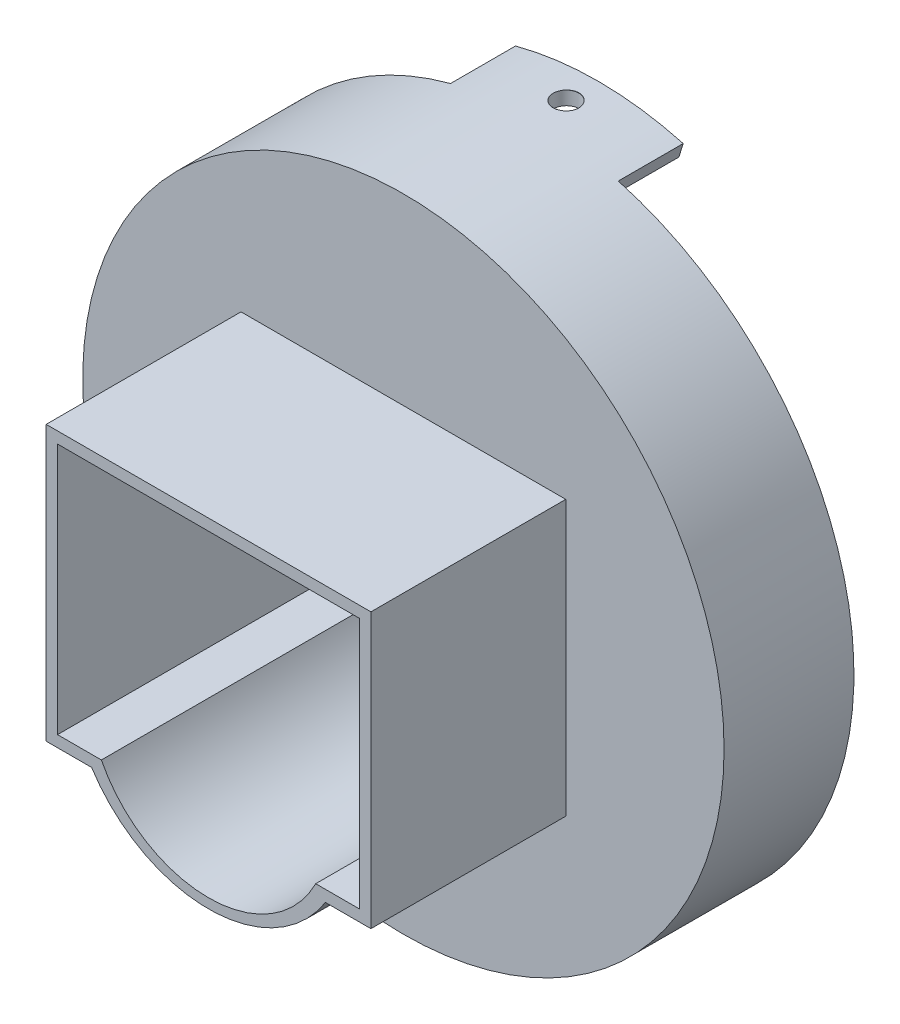
SolidWorks part; units mm, degrees
material "ABS"
ref_plane "Front Plane" through (0, 0, 0) normal (0, 0, 1) x (1, 0, 0)
ref_plane "Top Plane" through (0, 0, 0) normal (0, 1, 0) x (1, 0, 0)
ref_plane "Right Plane" through (0, 0, 0) normal (1, 0, 0) x (0, 0, -1)
sketch "Sketch1" plane through (0, 0, 0) normal (0, 0, 1) x (1, 0, 0)
  line L0 (16.764, -19.685) -> (23.622, -19.685)
  line L1 (-23.622, 19.685) -> (23.622, 19.685)
  line L2 (-23.622, 19.685) -> (-23.622, -19.685)
  line L3 (-23.622, -19.685) -> (-16.764, -19.685)
  line L4 (23.622, 19.685) -> (23.622, -19.685)
  line L5 (-23.622, 19.685) -> (23.622, -19.685) construction
  line L6 (-23.622, -19.685) -> (23.622, 19.685) construction
  circle A0 centre (0, 0) radius 50.165
  arc A1 (-16.764, -19.685) -> (16.764, -19.685) centre (0, -11.1845) ccw
  point P10 (0, 0)
  dimension "D1" = 100.33
  dimension "D5" = 18.796
  dimension "D2" = 47.244
  dimension "D3" = 39.37
  dimension "D4" = 6.858
extrude "Boss-Extrude1" add sketch "Sketch1" along normal blind 20.32
sketch "Sketch4" plane through (0, 0, 0) normal (0, 0, -1) x (-1, 0, 0)
  line L1 (-16.764, -19.685) -> (-23.622, -19.685)
  line L2 (-16.764, -19.685) -> (-16.764, 19.685)
  line L3 (-16.764, 19.685) -> (-23.622, 19.685)
  line L4 (-23.622, -19.685) -> (-23.622, 19.685)
  line L5 (16.764, -19.685) -> (23.622, -19.685)
  line L6 (16.764, -19.685) -> (16.764, 19.685)
  line L7 (16.764, 19.685) -> (23.622, 19.685)
  line L8 (23.622, -19.685) -> (23.622, 19.685)
extrude "Boss-Extrude3" add sketch "Sketch4" against normal blind 7.62
sketch "Sketch5" plane through (0, 0, 20.32) normal (0, 0, 1) x (1, 0, 0)
  line L0 (18.288, -21.463) -> (25.4, -21.463)
  line L1 (-25.4, -21.463) -> (-18.288, -21.463)
  line L2 (-25.4, -21.463) -> (-25.4, 21.463)
  line L3 (-25.4, 21.463) -> (25.4, 21.463)
  line L4 (25.4, -21.463) -> (25.4, 21.463)
  line L5 (-25.4, -21.463) -> (25.4, 21.463) construction
  line L6 (-25.4, 21.463) -> (25.4, -21.463) construction
  line L7 (-23.622, -19.685) -> (-16.764, -19.685)
  line L8 (-23.622, -19.685) -> (-23.622, 19.685)
  line L9 (-23.622, 19.685) -> (23.622, 19.685)
  line L10 (23.622, -19.685) -> (23.622, 19.685)
  line L11 (-23.622, -19.685) -> (23.622, 19.685) construction
  line L12 (-23.622, 19.685) -> (23.622, -19.685) construction
  line L14 (0, 0) -> (0, -31.496) construction
  line L15 (23.622, -19.685) -> (16.764, -19.685)
  arc A2 (-18.288, -21.463) -> (18.288, -21.463) centre (0, -9.812) ccw
  arc A4 (16.764, -19.685) -> (-16.764, -19.685) centre (0, -11.1845) cw
  point P0 (0, 0)
  point P6 (0, 0)
  dimension "D4" = 18.796
  dimension "D1" = 50.8
  dimension "D2" = 42.926
  dimension "D3" = 7.112
  dimension "D5" = 31.496
  dimension "D7" = 39.37
extrude "Boss-Extrude4" add sketch "Sketch5" along normal blind 30.48
sketch "Sketch6" plane through (0, 0, 20.32) normal (0, 0, 1) x (1, 0, 0)
  line L2 (13.8091, -48.2269) -> (13.4945, -45.9627)
  line L3 (-13.8091, -48.2269) -> (-13.1798, -46.0292)
  line L4 (-12.9425, 48.4667) -> (-12.5071, 46.2225)
  line L5 (13.2937, 48.3715) -> (12.6118, 46.1896)
  circle A1 centre (0, 0) radius 50.165 construction
  arc A2 (-12.5071, 46.2225) -> (12.6118, 46.1896) centre (-0.0029, 4.0748) cw
  arc A3 (13.8091, -48.2269) -> (-13.8091, -48.2269) centre (0, 0) cw
  arc A4 (-13.1798, -46.0292) -> (13.4945, -45.9627) centre (0.0422, 0.1474) ccw
  arc A5 (-12.9425, 48.4667) -> (13.2937, 48.3715) centre (0, 0) cw
  point P17 (0, -50.165)
  dimension "D4" = 2.286
  dimension "D1" = 2.286
  dimension "D2" = 2.286
  dimension "D3" = 2.286
extrude "Boss-Extrude5" add sketch "Sketch6" against normal blind 30.48
hole_wizard "Ø4.0mm Dowel Hole1" positions "3DSketch2" profile "Sketch8" hole size "Ø4.0" standard "ANSI Metric" end condition through all
sketch3d "3DSketch2"
  point P0 (0.0643, 50.165, -5.0537)
sketch "Sketch8" plane through (0.0643, 50.165, -5.0537) normal (0, 0, 1) x (-1, 0.0013, 0)
  line L0 (0, 0) -> (0, 100.3943)
  line L1 (0, 100.3943) -> (2, 100.3943)
  line L2 (2, 100.3943) -> (2, 0.021)
  line L3 (2, 0.021) -> (2.025, 0)
  line L5 (2.025, 0) -> (0, 0)
  line L6 (-2, 0.021) -> (-2.025, 0) construction
  line L11 (0, -6.35) -> (0, 107.95) construction
  dimension "Thru Hole Dia." = 4
  dimension "Thru Hole Depth" = 100.3943
  dimension "Near C'Sink Dia." = 4.05
  dimension "Near C'Sink Angle" = 100
